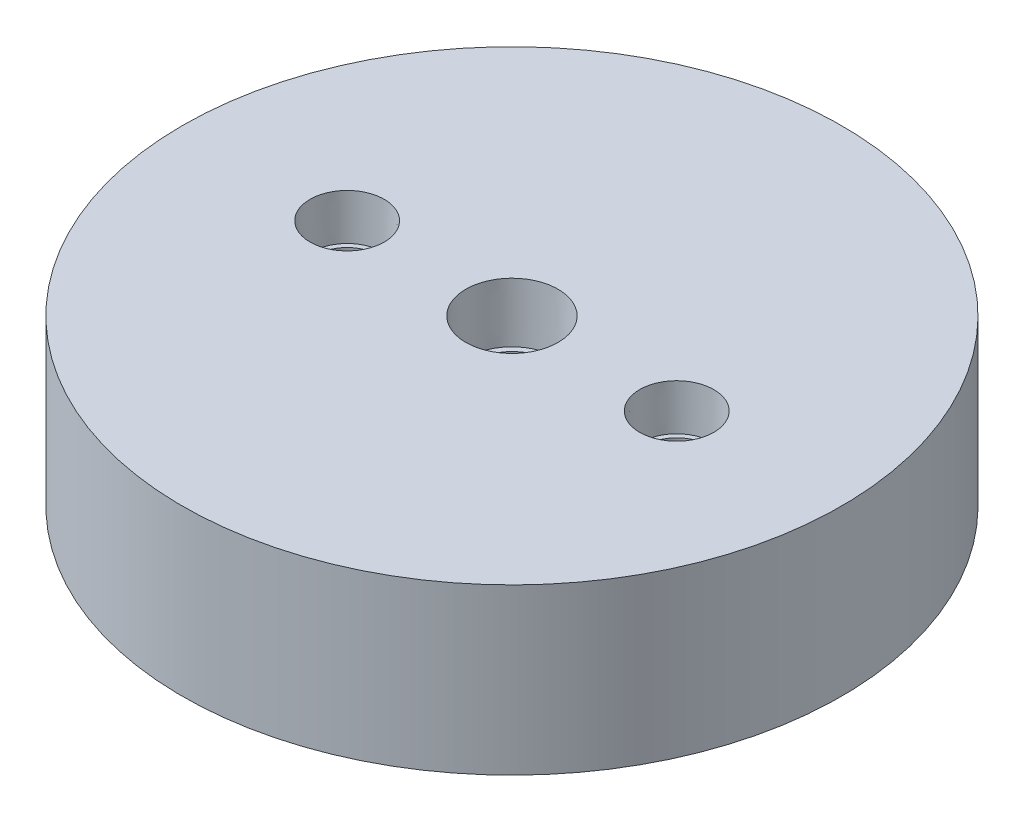
SolidWorks part; units mm, degrees
material "6061 Alloy"
ref_plane "Front Plane" through (0, 0, 0) normal (0, 0, 1) x (1, 0, 0)
ref_plane "Top Plane" through (0, 0, 0) normal (0, 1, 0) x (1, 0, 0)
ref_plane "Right Plane" through (0, 0, 0) normal (1, 0, 0) x (0, 0, -1)
sketch "Sketch1" plane through (0, 0, 0) normal (0, 0, 1) x (1, 0, 0)
  line L0 (0, 0) -> (-76.2, 0)
  line L1 (-76.2, 0) -> (-76.2, -38.1)
  line L2 (-76.2, -38.1) -> (-60.96, -38.1)
  line L3 (-60.96, -38.1) -> (-60.96, -32.258)
  line L4 (-60.96, -32.258) -> (-55.7149, -32.258)
  line L5 (0, 0) -> (0, -15.8572)
  line L8 (-28.575, -32.258) -> (-28.575, -27.178)
  line L9 (-28.575, -27.178) -> (-28.0924, -27.178)
  line L10 (-22.225, -27.178) -> (0, -15.8572)
  line L14 (-24.0284, -27.178) -> (-22.225, -27.178)
  line L18 (-51.6509, -32.258) -> (-32.164, -32.258)
  line L22 (-30.3647, -32.258) -> (-28.575, -32.258)
  line L23 (-32.164, -32.258) -> (-30.3647, -32.258)
  line L24 (-55.7149, -32.258) -> (-51.6509, -32.258)
  line L25 (-28.0924, -27.178) -> (-24.0284, -27.178)
  dimension "D1" = 76.2
  dimension "D2" = 38.1
  dimension "D3" = 15.24
  dimension "D4" = 5.842
  dimension "D5" = 32.385
  dimension "D6" = 15.8572
  dimension "D7" = 6.35
  dimension "D8" = 5.08
revolve "Revolve1" add sketch "Sketch1" angle 360 about L5
hole_wizard "1/2 NPT Tapped Hole1" positions "Sketch2" profile "Sketch3" size "1/2" standard "ANSI Inch" end condition through all
sketch "Sketch2" plane through (0, 0, 0) normal (0, 1, 0) x (1, 0, 0)
  point P0 (0, 0)
sketch "Sketch3" plane through (0, 0, 0) normal (1, 0, 0) x (0, 0, 1)
  line L0 (0, 0) -> (0, 38.1)
  line L1 (0, 38.1) -> (8.9281, 38.1)
  line L2 (-10.2617, 13.462) -> (-10.6647, 0) construction
  line L3 (8.9281, 38.1) -> (8.9281, 13.462)
  line L4 (8.9281, 13.462) -> (10.2617, 13.462)
  line L5 (10.2617, 13.462) -> (10.6647, 0)
  line L7 (10.6647, 0) -> (0, 0)
  line L8 (0, -6.35) -> (0, 107.95) construction
  line L11 (-8.9281, 13.462) -> (-10.2617, 13.462) construction
  dimension "Thru Tap Drill Dia." = 17.8562
  dimension "Thru Tap Drill Depth" = 38.1
  dimension "Thread Dia." = 21.3295
  dimension "Thread Angle" = 3.43
  dimension "Thread Depth" = 13.462
hole_wizard "3/8 NPT Tapped Hole1" positions "Sketch4" profile "Sketch5" size "3/8" standard "ANSI Inch" end condition through all
sketch "Sketch4" plane through (0, 0, 0) normal (0, 1, 0) x (1, 0, 0)
  point P0 (-38.1, 0)
  point P2 (38.1, 0)
  dimension "D1" = 38.1
  dimension "D2" = 38.1
sketch "Sketch5" plane through (-38.1, 0, 0) normal (1, 0, 0) x (0, 0, 1)
  line L0 (0, 0) -> (0, 38.1)
  line L1 (0, 38.1) -> (7.1374, 38.1)
  line L2 (-8.2632, 10.414) -> (-8.575, 0) construction
  line L3 (7.1374, 38.1) -> (7.1374, 10.414)
  line L4 (7.1374, 10.414) -> (8.2632, 10.414)
  line L5 (8.2632, 10.414) -> (8.575, 0)
  line L7 (8.575, 0) -> (0, 0)
  line L8 (0, -6.35) -> (0, 107.95) construction
  line L11 (-7.1374, 10.414) -> (-8.2632, 10.414) construction
  dimension "Thru Tap Drill Dia." = 14.2748
  dimension "Thru Tap Drill Depth" = 38.1
  dimension "Thread Dia." = 17.15
  dimension "Thread Angle" = 3.43
  dimension "Thread Depth" = 10.414
sketch "Sketch18" plane through (0, -32.258, 0) normal (0, -1, 0) x (1, 0, 0)
  line L0 (0, -44.45) -> (0, 44.45) construction
  circle A0 centre (0, 44.45) radius 1.27
  circle A1 centre (0, -44.45) radius 1.27
  dimension "D3" = 2.54
  dimension "D1" = 44.45
  dimension "D2" = 44.45
equation "\"D2@Sketch18\"=\"D1@Sketch18\""
